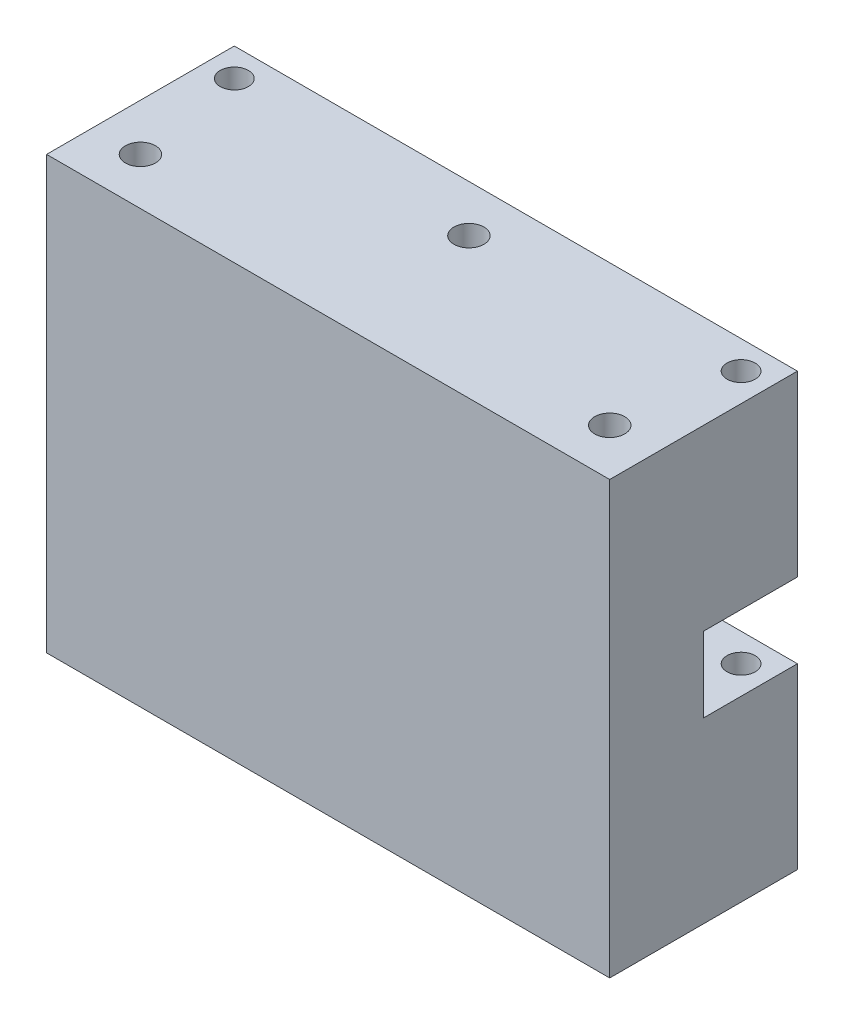
SolidWorks part; units mm, degrees
ref_plane "Front Plane" through (0, 0, 0) normal (0, 0, 1) x (1, 0, 0)
ref_plane "Top Plane" through (0, 0, 0) normal (0, 1, 0) x (1, 0, 0)
ref_plane "Right Plane" through (0, 0, 0) normal (1, 0, 0) x (0, 0, -1)
sketch "Sketch1" plane through (0, 0, 0) normal (0, 1, 0) x (1, 0, 0)
  line L1 (-30, 10) -> (30, 10)
  line L2 (-30, 10) -> (-30, -10)
  line L3 (-30, -10) -> (30, -10)
  line L4 (30, 10) -> (30, -10)
  line L5 (-30, 10) -> (30, -10) construction
  line L6 (-30, -10) -> (30, 10) construction
  point P0 (0, 0)
  dimension "D1" = 20
  dimension "D2" = 60
extrude "Boss-Extrude1" add sketch "Sketch1" along normal blind 46
sketch "Sketch2" plane through (30, 0, 0) normal (1, 0, 0) x (0, 0, -1)
  line L1 (10, 46) -> (10, 0) construction
  line L2 (-10, 23) -> (10, 23) construction
  line L3 (10, 19) -> (10, 27)
  line L4 (10, 27) -> (0, 27)
  line L5 (0, 19) -> (0, 27)
  line L6 (-10, 46) -> (-10, 0) construction
  line L7 (10, 19) -> (0, 19)
  point P0 (-2.7706, 23)
  point P10 (10, 22.5843)
  point P12 (0, 23)
  dimension "D1" = 8
  dimension "D2" = 10
extrude "Cut-Extrude1" cut sketch "Sketch2" against normal blind 10
hole_wizard "Ø3.0mm Dowel Hole1" positions "Sketch3" profile "Sketch4" hole size "Ø3.0" standard "ANSI Metric" end condition through all
sketch "Sketch3" plane through (0, 46, 0) normal (0, 1, 0) x (1, 0, 0)
  line L0 (0, 10) -> (0, -10) construction
  line L1 (30, 10) -> (-30, 10) construction
  line L2 (-30, -10) -> (30, -10) construction
  line L4 (30, -10) -> (30, 10) construction
  point P0 (-27, 7)
  point P11 (0, 0)
  point P12 (27, 7)
  dimension "D1" = 3
  dimension "D2" = 3
sketch "Sketch4" plane through (-27, 46, -7) normal (1, 0, 0) x (0, 0, 1)
  line L0 (0, 0) -> (0, 46)
  line L1 (0, 46) -> (1.5, 46)
  line L2 (1.5, 46) -> (1.5, 0)
  line L5 (1.5, 0) -> (0, 0)
  line L11 (0, -6.35) -> (0, 107.95) construction
  dimension "Thru Hole Dia." = 3
  dimension "Thru Hole Depth" = 46
sketch "Sketch5" plane through (-30, 0, 0) normal (-1, 0, 0) x (0, 0, 1)
  line L0 (-10, 23) -> (10, 23) construction
  line L1 (-10, 46) -> (-10, 0) construction
  line L2 (10, 46) -> (10, 0) construction
  line L3 (-10, 28) -> (0, 28)
  line L4 (0, 28) -> (0, 18)
  line L5 (-10, 28) -> (-10, 18)
  line L6 (-10, 18) -> (0, 18)
  point P11 (0, 23)
  dimension "D1" = 10
  dimension "D2" = 10
extrude "Cut-Extrude2" cut sketch "Sketch5" against normal blind 10
hole_wizard "M3 Clearance Hole1" positions "Sketch6" profile "Sketch7" hole size "M3" standard "ANSI Metric" end condition through all
sketch "Sketch6" plane through (0, 46, 0) normal (0, 1, 0) x (1, 0, 0)
  line L0 (0, -10) -> (0, 10) construction
  line L1 (-30, -10) -> (30, -10) construction
  line L2 (30, 10) -> (-30, 10) construction
  point P0 (-25, -5)
  point P2 (0, 5)
  point P12 (0, 0)
  point P13 (25, -5)
  point P14 (0, 0)
  dimension "D1" = 5
  dimension "D2" = 5
  dimension "D3" = 50
sketch "Sketch7" plane through (-25, 46, 5) normal (1, 0, 0) x (0, 0, 1)
  line L0 (0, 0) -> (0, 46)
  line L1 (0, 46) -> (1.6, 46)
  line L2 (1.6, 46) -> (1.6, 0)
  line L5 (1.6, 0) -> (0, 0)
  line L11 (0, -6.35) -> (0, 107.95) construction
  dimension "Thru Hole Dia." = 3.2
  dimension "Thru Hole Depth" = 46
